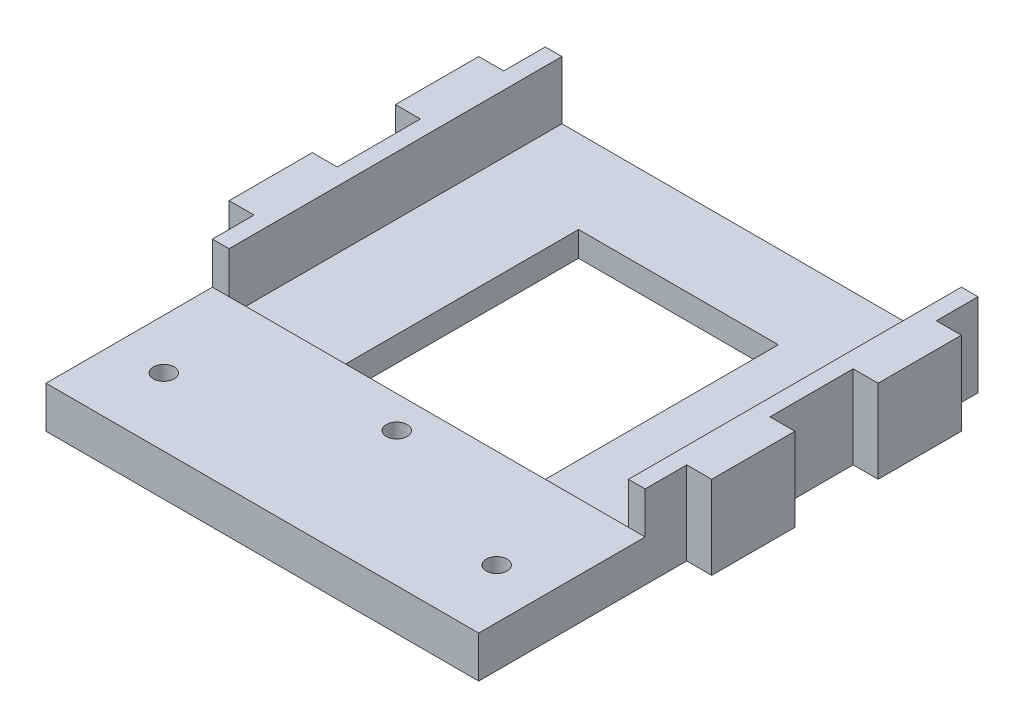
SolidWorks part; units mm, degrees
ref_plane "Front Plane" through (0, 0, 0) normal (0, 0, 1) x (1, 0, 0)
ref_plane "Top Plane" through (0, 0, 0) normal (0, 1, 0) x (1, 0, 0)
ref_plane "Right Plane" through (0, 0, 0) normal (1, 0, 0) x (0, 0, -1)
sketch "Sketch1" plane through (0, 0, 0) normal (0, 1, 0) x (1, 0, 0)
  line L1 (-26, -30) -> (26, -30)
  line L2 (-26, -30) -> (-26, 30)
  line L3 (-26, 30) -> (26, 30)
  line L4 (26, -30) -> (26, 30)
  line L5 (-26, -30) -> (26, 30) construction
  line L6 (-26, 30) -> (26, -30) construction
  point P0 (0, 0)
  dimension "D1" = 52
  dimension "D2" = 60
extrude "Boss-Extrude1" add sketch "Sketch1" along normal blind 10
sketch "Sketch2" plane through (0, 10, 0) normal (0, 1, 0) x (1, 0, 0)
  line L0 (26, -30) -> (26, 30) construction
  line L1 (-26, -30) -> (26, -30)
  line L2 (-26, -30) -> (-26, -10)
  line L3 (-26, -10) -> (-24, -10)
  line L4 (26, -30) -> (26, -10)
  line L5 (26, 30) -> (-26, 30) construction
  line L7 (-24, -10) -> (-24, 30)
  line L8 (-24, 30) -> (24, 30)
  line L9 (24, -10) -> (24, 30)
  line L10 (0, 0) -> (0, 30) construction
  line L11 (-26, 30) -> (-26, -30) construction
  line L12 (24, -10) -> (26, -10)
  dimension "D1" = 20
  dimension "D2" = 2
extrude "Cut-Extrude1" cut sketch "Sketch2" against normal blind 5
sketch "Sketch3" plane through (0, 5, 0) normal (0, 1, 0) x (1, 0, 0)
  line L0 (20, -21.8476) -> (-20, -21.8476) construction
  line L1 (0, 0) -> (0, -16.8476) construction
  circle A0 centre (-20, -21.8476) radius 1.25
  circle A1 centre (0, -13.8476) radius 1.25
  circle A2 centre (20, -21.8476) radius 1.25
  circle A3 centre (-20, -21.8476) radius 1.5 construction
  circle A4 centre (0, -13.8476) radius 1.2195 construction
  dimension "D1" = 2.5
  dimension "D4" = 40
extrude "Cut-Extrude2" cut sketch "Sketch3" against normal blind 5
sketch "Sketch5" plane through (0, 0, 0) normal (0, -1, 0) x (1, 0, 0)
  line L1 (-18.375, 24.6621) -> (-21.625, 24.6621)
  line L2 (-21.625, 24.6621) -> (-23.25, 21.8476)
  line L3 (-23.25, 21.8476) -> (-21.625, 19.033)
  line L4 (-21.625, 19.033) -> (-18.375, 19.033)
  line L5 (-18.375, 19.033) -> (-16.75, 21.8476)
  line L6 (-16.75, 21.8476) -> (-18.375, 24.6621)
  line L7 (1.625, 16.6621) -> (-1.625, 16.6621)
  line L8 (-1.625, 16.6621) -> (-3.25, 13.8476)
  line L9 (-3.25, 13.8476) -> (-1.625, 11.033)
  line L10 (-1.625, 11.033) -> (1.625, 11.033)
  line L11 (1.625, 11.033) -> (3.25, 13.8476)
  line L12 (3.25, 13.8476) -> (1.625, 16.6621)
  line L13 (21.625, 24.6621) -> (18.375, 24.6621)
  line L14 (18.375, 24.6621) -> (16.75, 21.8476)
  line L15 (16.75, 21.8476) -> (18.375, 19.033)
  line L16 (18.375, 19.033) -> (21.625, 19.033)
  line L17 (21.625, 19.033) -> (23.25, 21.8476)
  line L18 (23.25, 21.8476) -> (21.625, 24.6621)
  circle A2 centre (-20, 21.8476) radius 3.25
  circle A3 centre (-20, 21.8476) radius 3.25 construction
  circle A5 centre (0, 13.8476) radius 3.25
  circle A6 centre (0, 13.8476) radius 3.25 construction
  circle A7 centre (-20, 21.8476) radius 2.8146 construction
  circle A8 centre (20, 21.8476) radius 3.25
  circle A9 centre (20, 21.8476) radius 3.25 construction
  circle A10 centre (0, 13.8476) radius 2.8146 construction
  circle A11 centre (20, 21.8476) radius 2.8146 construction
  dimension "D1" = 2
  dimension "D2" = 2
  dimension "D3" = 2
extrude "Cut-Extrude3" cut sketch "Sketch5" against normal blind 3
sketch "Sketch6" plane through (0, 0, 0) normal (0, -1, 0) x (1, 0, 0)
  line L0 (-26, 30) -> (26, 30) construction
  line L1 (-12, -20) -> (12, -20)
  line L2 (-12, -20) -> (-12, 10)
  line L3 (-12, 10) -> (12, 10)
  line L4 (12, -20) -> (12, 10)
  line L5 (-12, -20) -> (12, 10) construction
  line L6 (-12, 10) -> (12, -20) construction
  line L7 (0, -5) -> (0, 0) construction
  point P0 (0, 0)
  dimension "D1" = 20
  dimension "D2" = 30
  dimension "D3" = 24
extrude "Cut-Extrude4" cut sketch "Sketch6" against normal through all
sketch "Sketch7" plane through (0, 10, 0) normal (0, 1, 0) x (1, 0, 0)
  line L1 (-26, 25) -> (-29, 25)
  line L2 (-26, 25) -> (-26, 15)
  line L3 (-26, 15) -> (-29, 15)
  line L4 (-29, 25) -> (-29, 15)
  line L5 (-24, 30) -> (-26, 30) construction
  dimension "D1" = 3
  dimension "D2" = 10
  dimension "D3" = 5
extrude "Boss-Extrude2" add sketch "Sketch7" against normal blind 10
pattern_linear "LPattern1" count 2 spacing 20 along (0, 0, 1) of "Boss-Extrude2"
mirror "Mirror1" about plane through (0, 0, 0) normal (1, 0, 0) of "LPattern1", "Boss-Extrude2"
sketch "Sketch8" plane through (0, 5, 0) normal (0, 1, 0) x (1, 0, 0)
  line L1 (-24, 30) -> (24, 30)
  line L2 (-24, 30) -> (-24, -10)
  line L3 (-24, -10) -> (24, -10)
  line L4 (24, 30) -> (24, -10)
extrude "Cut-Extrude5" cut sketch "Sketch8" against normal blind 2
